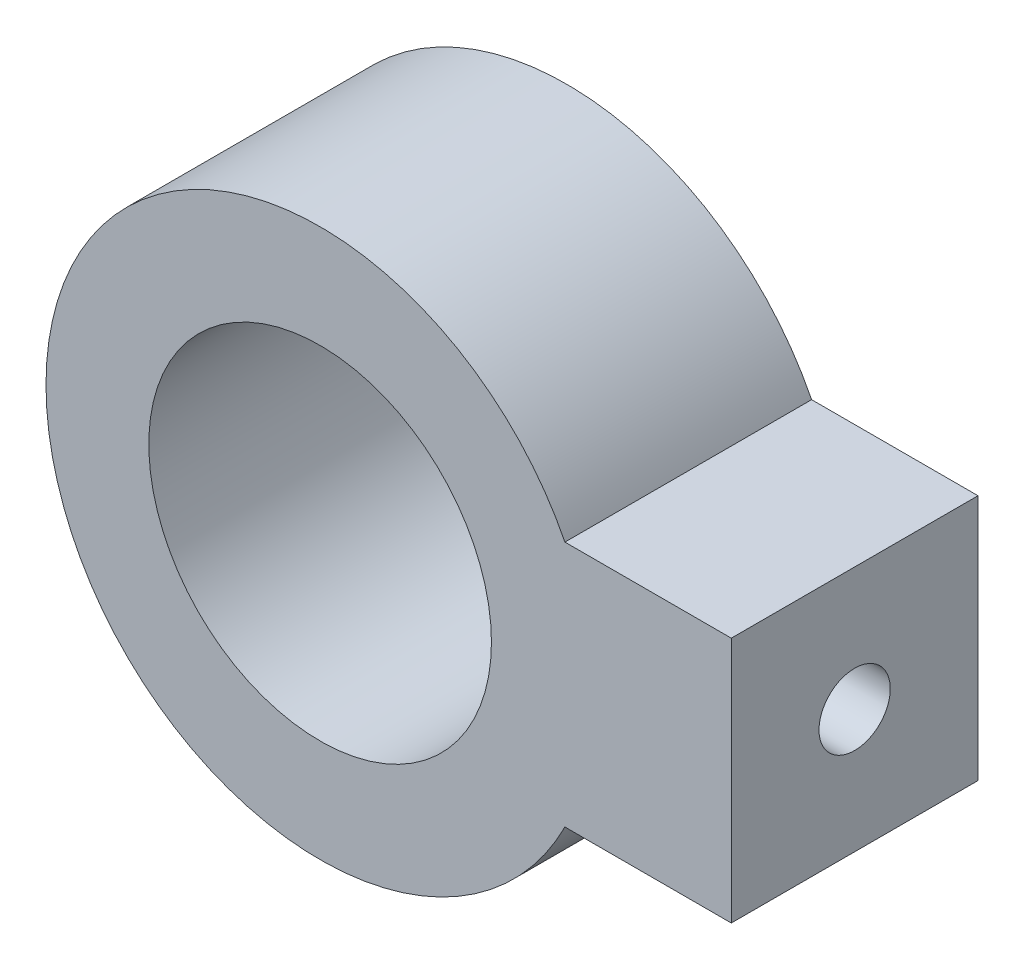
SolidWorks part; units mm, degrees
ref_plane "Front Plane" through (0, 0, 0) normal (0, 0, 1) x (1, 0, 0)
ref_plane "Top Plane" through (0, 0, 0) normal (0, 1, 0) x (1, 0, 0)
ref_plane "Right Plane" through (0, 0, 0) normal (1, 0, 0) x (0, 0, -1)
sketch "Sketch1" plane through (0, 0, 0) normal (0, 0, 1) x (1, 0, 0)
  circle A0 centre (0, 0) radius 10
  circle A1 centre (0, 0) radius 6.25
  dimension "CollarBore" = 12.5
extrude "Collar_ring" add sketch "Sketch1" along normal blind 9
sketch "Sketch2" plane through (0, 0, 0) normal (0, 0, 1) x (1, 0, 0)
  line L0 (8, -4.5) -> (15, -4.5)
  line L1 (15, -4.5) -> (15, 4.5)
  line L2 (15, 4.5) -> (8, 4.5)
  line L3 (8, 4.5) -> (8, -4.5)
extrude "Screw_boss" add sketch "Sketch2" along normal blind 9
ref_plane "Plane_X+10.50" through (10.5, 0, 0) normal (1, 0, 0) x (0, 0, -1)
sketch "Sketch3" plane through (10.5, 0, 0) normal (1, 0, 0) x (0, 0, -1)
  circle A0 centre (-4.5, 0) radius 1.3
extrude "M3_thumb_screw_hole" cut sketch "Sketch3" against normal mid plane 11
